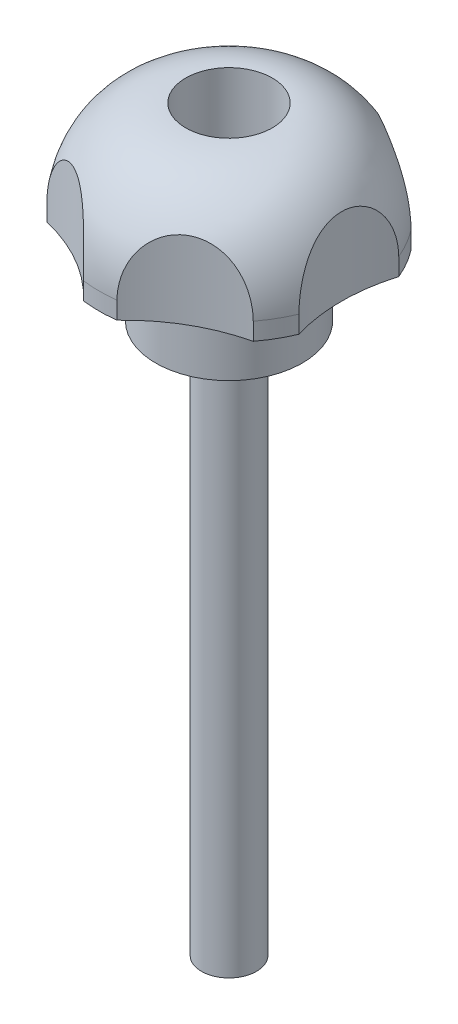
SolidWorks part; units mm, degrees
ref_plane "Alzado" through (0, 0, 0) normal (0, 0, 1) x (1, 0, 0)
ref_plane "Planta" through (0, 0, 0) normal (0, 1, 0) x (1, 0, 0)
ref_plane "Vista lateral" through (0, 0, 0) normal (1, 0, 0) x (0, 0, -1)
sketch "Croquis2" plane through (0, 0, 0) normal (0, 0, 1) x (1, 0, 0)
  line L0 (4.7625, 95.25) -> (12.7, 95.25)
  line L1 (0, 0) -> (4.7625, 0)
  line L2 (0, 0) -> (0, 115.25)
  line L3 (12.7, 95.25) -> (12.7, 112.95)
  line L4 (4.7625, 0) -> (4.7625, 95.25)
  line L5 (7.5, 115.25) -> (0, 115.25)
  line L6 (13.4838, 112.95) -> (-49986.5162, 112.95) construction
  line L8 (18.5027, 107.95) -> (22.5, 107.95)
  line L9 (22.5, 107.95) -> (22.5, 110.9649)
  line L10 (0, 150) -> (0, 50150) construction
  line L11 (-3.9035, 127.95) -> (49996.0965, 127.95) construction
  line L12 (18.5027, 104.297) -> (18.5027, 50104.297) construction
  line L13 (7.5, 127.95) -> (7.5, 115.25)
  spline S0 degree 2 poles (12.7, 112.95) (18.5027, 112.95) (18.5027, 107.95) knots 0 0 0 1 1 1
  spline S1 degree 3 poles (7.5, 127.95) (17.075, 127.95) (22.5, 119.4672) (22.5, 110.9649) knots 0 0 0 0 1 1 1 1
  dimension "D5" = 3.9973
  dimension "D4" = 20
  dimension "D1" = 95.25
  dimension "D2" = 4.7625
  dimension "D3" = 20
  dimension "D6" = 22.5
  dimension "D7" = 7.5
  dimension "D8" = 12.7
  dimension "D9" = 15
  dimension "D10" = 12.7
revolve "Revolución1" add sketch "Croquis2" angle 360 about L2
sketch "Croquis3" plane through (0, 107.95, 0) normal (0, -1, 0) x (1, 0, 0)
  arc A0 (20.7727, 8.6454) -> (20.7727, -8.6454) centre (49.5, 0) ccw
  circle A1 centre (0, 0) radius 22.5 construction
  arc A2 (20.7727, 8.6454) -> (20.7727, -8.6454) centre (0, 0) cw
  arc A3 (17.8735, -13.667) -> (2.8992, -22.3124) centre (24.75, -42.8683) ccw
  arc A4 (17.8735, -13.667) -> (2.8992, -22.3124) centre (0, 0) cw
  arc A5 (-2.8992, -22.3124) -> (-17.8735, -13.667) centre (-24.75, -42.8683) ccw
  arc A6 (-2.8992, -22.3124) -> (-17.8735, -13.667) centre (0, 0) cw
  arc A7 (-20.7727, -8.6454) -> (-20.7727, 8.6454) centre (-49.5, 0) ccw
  arc A8 (-20.7727, -8.6454) -> (-20.7727, 8.6454) centre (0, 0) cw
  arc A9 (-17.8735, 13.667) -> (-2.8992, 22.3124) centre (-24.75, 42.8683) ccw
  arc A10 (-17.8735, 13.667) -> (-2.8992, 22.3124) centre (0, 0) cw
  arc A11 (2.8992, 22.3124) -> (17.8735, 13.667) centre (24.75, 42.8683) ccw
  arc A12 (2.8992, 22.3124) -> (17.8735, 13.667) centre (0, 0) cw
  point P5 (19.5, 0)
  point P10 (22.5, 0)
  point P15 (11.25, -19.4856)
  point P19 (-11.25, -19.4856)
  point P23 (-22.5, 0)
  point P27 (-11.25, 19.4856)
  point P31 (11.25, 19.4856)
  point P32 (0, 0)
  dimension "D1" = 30
  dimension "D3" = 6
  dimension "D2" = 3
extrude "Cortar-Extruir1" cut sketch "Croquis3" against normal through all
